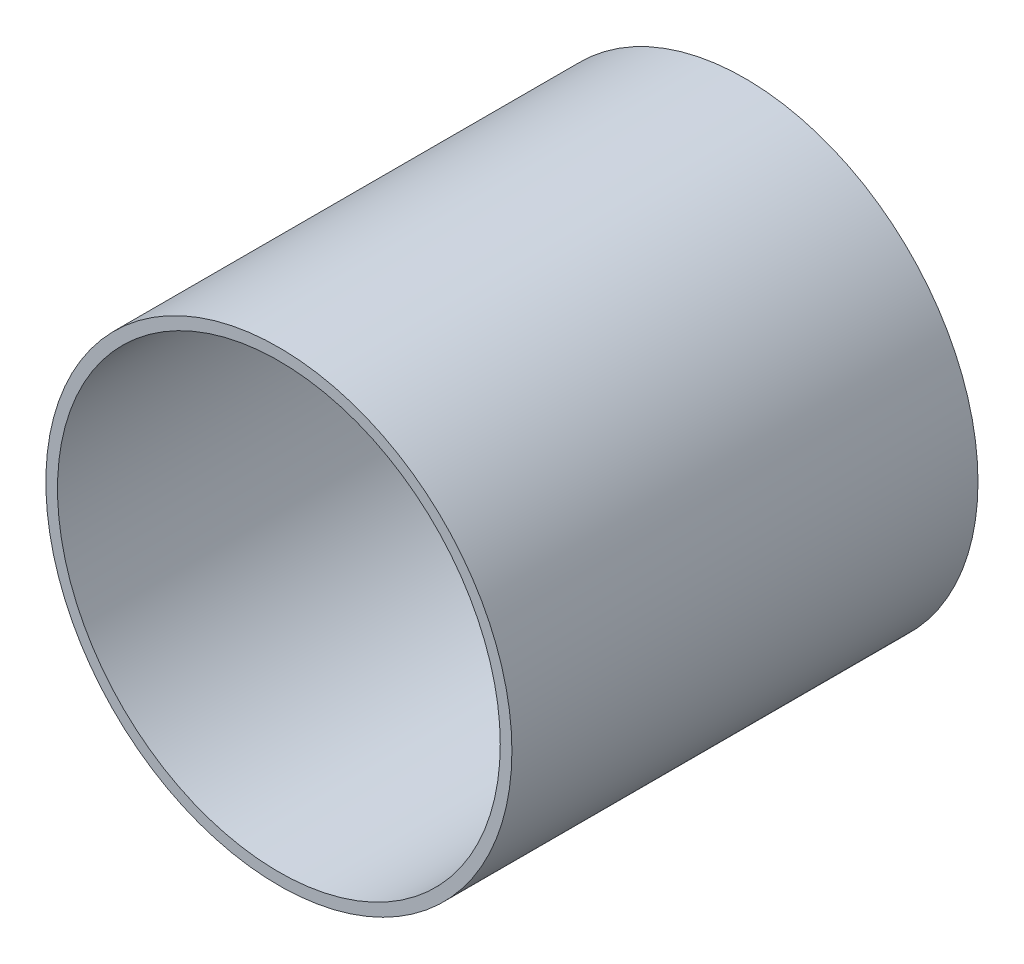
SolidWorks part; units mm, degrees
material "PVC Rigid"
ref_plane "Front Plane" through (0, 0, 0) normal (0, 0, 1) x (1, 0, 0)
ref_plane "Top Plane" through (0, 0, 0) normal (0, 1, 0) x (1, 0, 0)
ref_plane "Right Plane" through (0, 0, 0) normal (1, 0, 0) x (0, 0, -1)
sketch "Sketch1" plane through (0, 0, 0) normal (0, 0, 1) x (1, 0, 0)
  circle A0 centre (0, 0) radius 50.8
  circle A1 centre (0, 0) radius 48.26
  dimension "D1" = 101.6
  dimension "D2" = 2.54
extrude "Boss-Extrude1" add sketch "Sketch1" along normal mid plane 101.6
